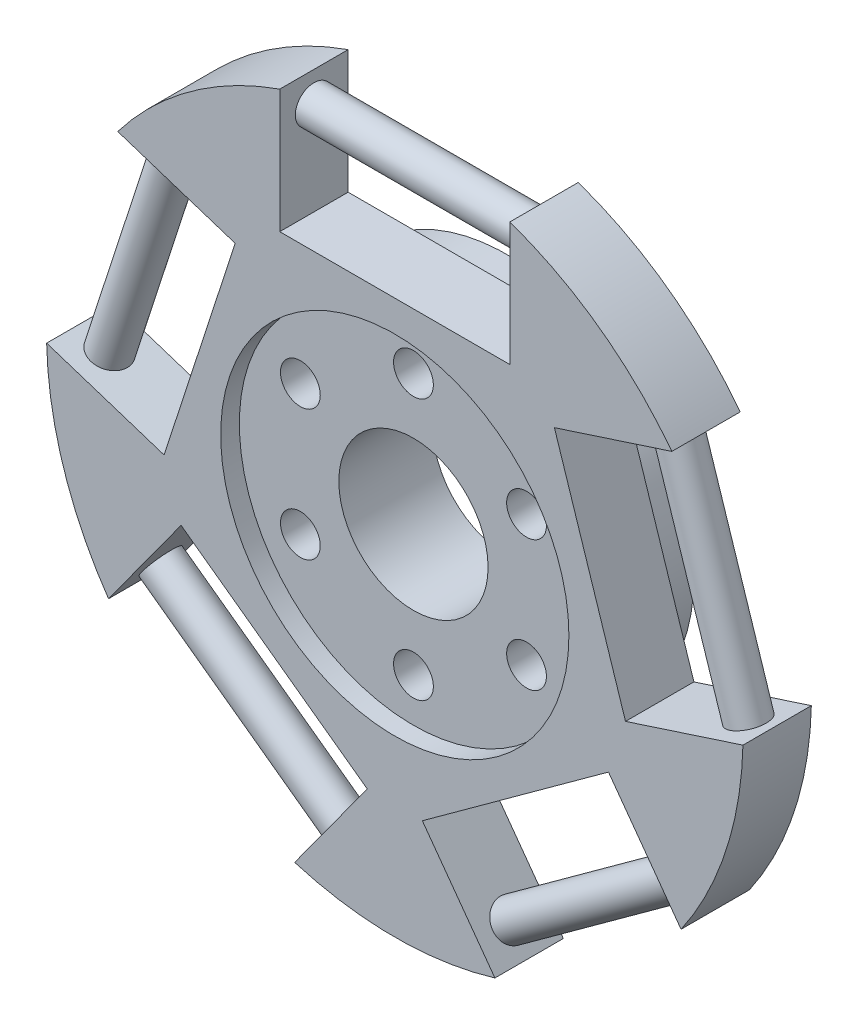
SolidWorks part; units mm, degrees
ref_plane "前视基准面" through (0, 0, 0) normal (0, 0, 1) x (1, 0, 0)
ref_plane "上视基准面" through (0, 0, 0) normal (0, 1, 0) x (1, 0, 0)
ref_plane "右视基准面" through (0, 0, 0) normal (1, 0, 0) x (0, 0, -1)
sketch "草图1" plane through (0, 0, 0) normal (0, 0, 1) x (1, 0, 0)
  circle A0 centre (0, 0) radius 28
  circle A1 centre (0, 0) radius 6
  dimension "D1" = 56
  dimension "D2" = 12
extrude "凸台-拉伸1" add sketch "草图1" along normal blind 5.5
sketch "草图2" plane through (0, 0, 5.5) normal (0, 0, 1) x (1, 0, 0)
  line L0 (0, 0) -> (0, 30) construction
  line L1 (-9.25, 30) -> (9.25, 30)
  line L2 (-9.25, 30) -> (-9.25, 16.5)
  line L3 (-9.25, 16.5) -> (9.25, 16.5)
  line L4 (9.25, 30) -> (9.25, 16.5)
  line L5 (-9.25, 23.25) -> (9.25, 23.25) construction
  line L6 (-9.25, 17) -> (9.25, 17) construction
  circle A0 centre (0, 0) radius 6 construction
  dimension "D4" = 30
  dimension "D1" = 16.5
  dimension "D2" = 13.5
  dimension "D3" = 18.5
  dimension "D6" = 13
  dimension "D7" = 17
  dimension "D8" = 6.75
extrude "切除-拉伸1" cut sketch "草图2" against normal blind 6
sketch "草图3" plane through (-9.25, 0, 0) normal (1, 0, 0) x (0, 0, -1)
  line L0 (-2.75, 24) -> (-2.75, 26.428) construction
  line L1 (0, 26.428) -> (-5.5, 26.428) construction
  circle A0 centre (-2.75, 24) radius 1.5
  dimension "D1" = 3
  dimension "D2" = 24
extrude "凸台-拉伸2" add sketch "草图3" along direction (1, 0, 0) on the side of the normal up to surface (18.5 mm away) contours A0
pattern_circular "阵列(圆周)1" count 5 over 360 about axis through (0, 0, 0) along (0, 0, 1) of "切除-拉伸1", "凸台-拉伸2"
sketch "草图4" plane through (0, 0, 0) normal (0, 0, -1) x (-1, 0, 0)
  circle A0 centre (0, 0) radius 6
  circle A1 centre (0, 0) radius 15
  circle A2 centre (0, 0) radius 6 construction
  dimension "D1" = 30
extrude "凸台-拉伸3" add sketch "草图4" along normal blind 3.55
sketch "草图10" plane through (0, 0, 5.5) normal (0, 0, 1) x (1, 0, 0)
  circle A0 centre (0, 0) radius 14
  dimension "D1" = 28
extrude "切除-拉伸5" cut sketch "草图10" against normal blind 1.5
sketch "草图11" plane through (0, 0, 4) normal (0, 0, 1) x (1, 0, 0)
  circle A0 centre (0, 0) radius 10.5 construction
  circle A1 centre (0, -10.5) radius 1.6
  dimension "D1" = 3.2
  dimension "D2" = 21
extrude "切除-拉伸6" cut sketch "草图11" against normal blind 10
pattern_circular "阵列(圆周)2" count 6 over 360 about axis through (0, 0, 0) along (0, 0, 1) of "切除-拉伸6"
